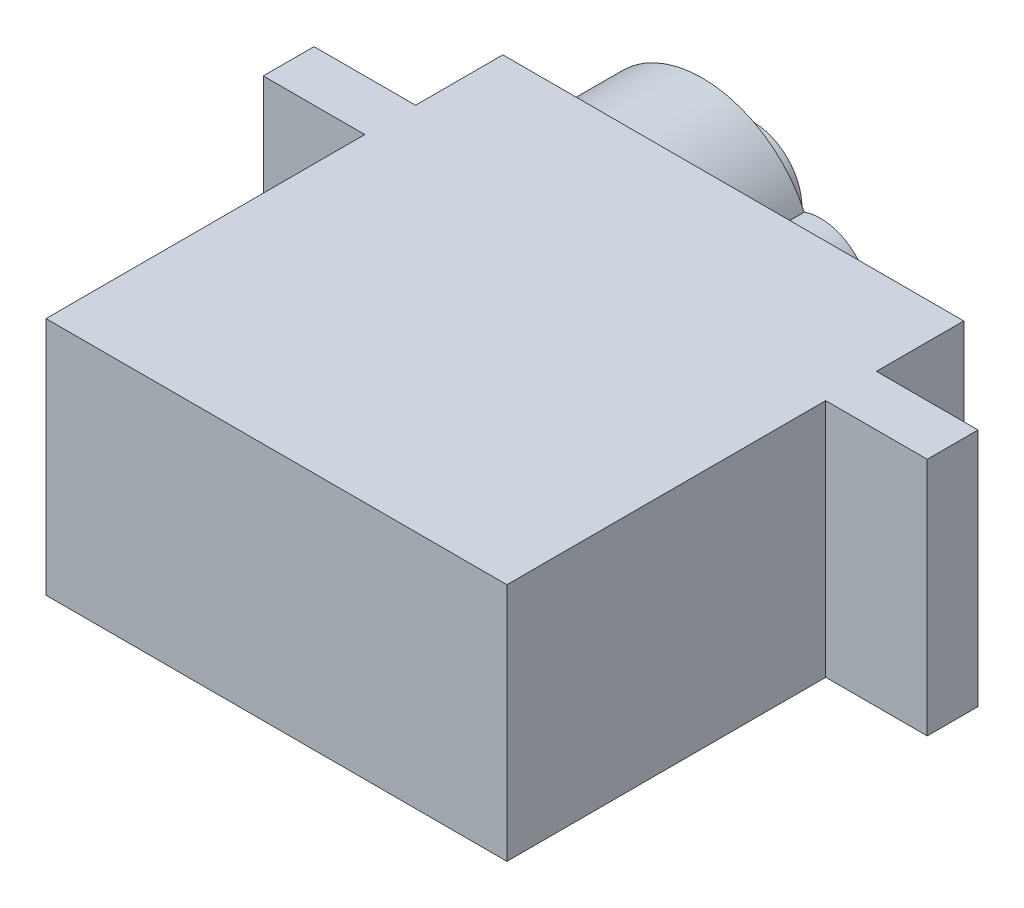
SolidWorks part; units mm, degrees
ref_plane "Alzado" through (0, 0, 0) normal (0, 0, 1) x (1, 0, 0)
ref_plane "Planta" through (0, 0, 0) normal (0, 1, 0) x (1, 0, 0)
ref_plane "Vista lateral" through (0, 0, 0) normal (1, 0, 0) x (0, 0, -1)
sketch "Croquis3" plane through (0, 0, 0) normal (0, 1, 0) x (1, 0, 0)
  line L0 (-11.35, 11.25) -> (11.35, 11.25)
  line L1 (11.35, 11.25) -> (11.35, 6.95)
  line L2 (11.35, 6.95) -> (16.35, 6.95)
  line L3 (16.35, 6.95) -> (16.35, 4.45)
  line L4 (16.35, 4.45) -> (11.35, 4.45)
  line L5 (11.35, 4.45) -> (11.35, -11.25)
  line L6 (11.35, -11.25) -> (-11.35, -11.25)
  line L7 (-11.35, -11.25) -> (-11.35, 4.45)
  line L8 (-11.35, 4.45) -> (-16.35, 4.45)
  line L9 (-16.35, 4.45) -> (-16.35, 6.95)
  line L10 (-16.35, 6.95) -> (-11.35, 6.95)
  line L11 (-11.35, 6.95) -> (-11.35, 11.25)
  line L12 (0, 0) -> (0, 22.3612) construction
  line L13 (7.461, 11.25) -> (7.461, -11.25) construction
  line L14 (7.461, 0) -> (0, 0) construction
  point P15 (0, 11.25)
  point P21 (0, 0)
  dimension "D1" = 22.7
  dimension "D2" = 5
  dimension "D3" = 5
  dimension "D4" = 2.5
  dimension "D5" = 2.5
  dimension "D6" = 4.3
  dimension "D7" = 4.3
  dimension "D8" = 15.7
  dimension "D9" = 22.7
extrude "Saliente-Extruir1" add sketch "Croquis3" along normal blind 11.8 contours L11 L0 L1 L2 L3 L4 L5 L6 L7 L8 L9 L10
sketch "Croquis7" plane through (0, 0, -11.25) normal (0, 0, -1) x (-1, 0, 0)
  line L0 (5.825, 11.8) -> (5.825, 0) construction
  line L1 (11.35, 11.8) -> (-11.35, 11.8) construction
  line L2 (11.35, 0) -> (-11.35, 0) construction
  line L3 (0, 0) -> (0, 11.8) construction
  line L4 (11.35, 11.8) -> (11.35, 0) construction
  circle A0 centre (5.825, 5.9) radius 5.525
  circle A1 centre (0, 5.9) radius 2.45
  point P13 (0, 0)
  dimension "D1" = 11.05
  dimension "D2" = 4.9
extrude "Saliente-Extruir2" add sketch "Croquis7" along normal blind 4.3 contours A0 A1 | A1 A0 | A0 A1
sketch "Croquis8" plane through (0, 0, -15.55) normal (0, 0, -1) x (-1, 0, 0)
  line L0 (5.825, 11.425) -> (5.825, 0.375) construction
  arc A0 (11.35, 5.9) -> (0.8075, 8.2131) centre (5.825, 5.9) ccw construction
  arc A1 (0.8075, 3.5869) -> (0.8075, 8.2131) centre (5.825, 5.9) ccw construction
  arc A2 (0.8075, 3.5869) -> (11.35, 5.9) centre (5.825, 5.9) ccw construction
  circle A3 centre (5.825, 5.9) radius 2.4
  circle A4 centre (5.825, 5.9) radius 0.575
  dimension "D1" = 4.8
  dimension "D2" = 1.15
extrude "Saliente-Extruir4" add sketch "Croquis8" along normal blind 2.5 contours L0 A3 A4 | A3 L0 A4
